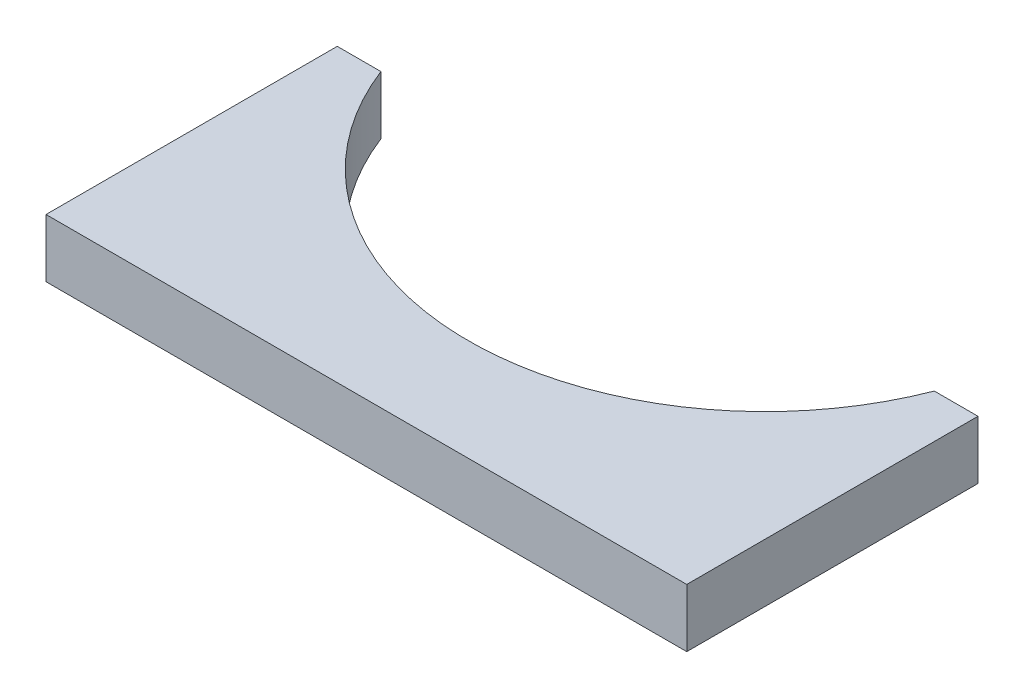
SolidWorks part; units mm, degrees
ref_plane "Front Plane" through (0, 0, 0) normal (0, 0, 1) x (1, 0, 0)
ref_plane "Top Plane" through (0, 0, 0) normal (0, 1, 0) x (1, 0, 0)
ref_plane "Right Plane" through (0, 0, 0) normal (1, 0, 0) x (0, 0, -1)
sketch "Sketch1" plane through (0, 0, 0) normal (0, 1, 0) x (1, 0, 0)
  line L0 (0, 19.8678) -> (0, -17.5304) construction
  line L1 (13.97, 0) -> (-13.97, 0)
  line L2 (-13.97, 0) -> (-13.97, 12.7)
  line L3 (-13.97, 12.7) -> (-12.065, 12.7)
  line L4 (13.97, 0) -> (13.97, 12.7)
  line L5 (13.97, 12.7) -> (12.065, 12.7)
  arc A2 (-12.065, 12.7) -> (12.065, 12.7) centre (0, 17.382) ccw
  point P10 (0, 0)
  dimension "D1" = 13.97
  dimension "D2" = 12.7
  dimension "D3" = 1.905
extrude "Boss-Extrude1" add sketch "Sketch1" along normal blind 2.54
